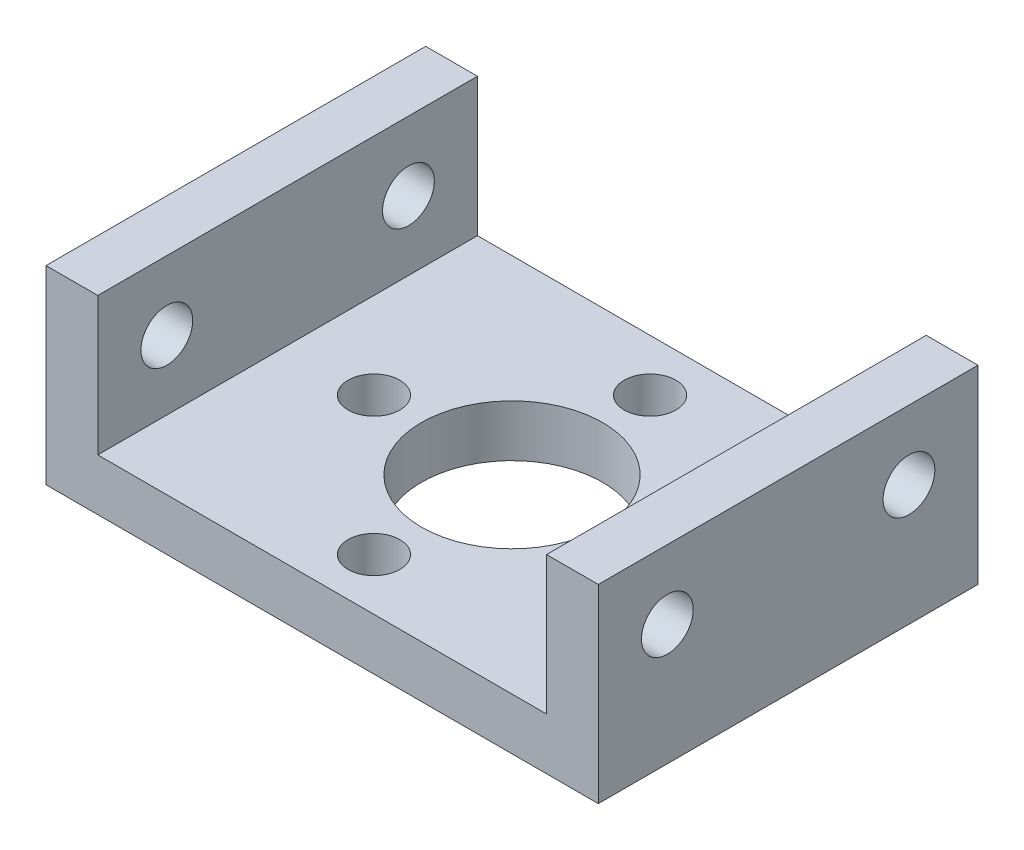
SolidWorks part; units mm, degrees
material "6061 合金"
ref_plane "前视基准面" through (0, 0, 0) normal (0, 0, 1) x (1, 0, 0)
ref_plane "上视基准面" through (0, 0, 0) normal (0, 1, 0) x (1, 0, 0)
ref_plane "右视基准面" through (0, 0, 0) normal (1, 0, 0) x (0, 0, -1)
sketch "草图1" plane through (0, 0, 0) normal (0, 1, 0) x (1, 0, 0)
  line L1 (-16, -11) -> (16, -11)
  line L2 (-16, -11) -> (-16, 11)
  line L3 (-16, 11) -> (16, 11)
  line L4 (16, -11) -> (16, 11)
  line L5 (-16, -11) -> (16, 11) construction
  line L6 (-16, 11) -> (16, -11) construction
  point P0 (0, 0)
  dimension "D1" = 32
  dimension "D2" = 22
extrude "凸台-拉伸1" add sketch "草图1" along normal blind 3
sketch "草图2" plane through (0, 3, 0) normal (0, 1, 0) x (1, 0, 0)
  line L0 (-16, -11) -> (16, -11) construction
  line L1 (-16, 11) -> (-13, 11)
  line L2 (-16, 11) -> (-16, -11)
  line L3 (-16, -11) -> (-13, -11)
  line L4 (-13, 11) -> (-13, -11)
  line L6 (16, 11) -> (13, 11)
  line L7 (16, 11) -> (16, -11)
  line L8 (16, -11) -> (13, -11)
  line L9 (13, 11) -> (13, -11)
  dimension "D1" = 3
  dimension "D2" = 3
extrude "凸台-拉伸2" add sketch "草图2" along normal blind 8
sketch "草图3" plane through (16, 0, 0) normal (1, 0, 0) x (0, 0, -1)
  line L0 (0, 11) -> (0, 7) construction
  line L1 (-11, 11) -> (11, 11) construction
  line L2 (-7, 7) -> (7, 7) construction
  circle A0 centre (-7, 7) radius 1.5
  circle A1 centre (7, 7) radius 1.5
  dimension "D3" = 3
  dimension "D4" = 3
  dimension "D1" = 14
  dimension "D2" = 4
extrude "切除-拉伸1" cut sketch "草图3" against normal through all
sketch "草图4" plane through (0, 3, 0) normal (0, 1, 0) x (1, 0, 0)
  circle A0 centre (0, 0) radius 5.25
  circle A1 centre (0, 0) radius 8 construction
  circle A2 centre (0, 8) radius 1.5
  circle A4 centre (8, 0) radius 1.5
  circle A5 centre (0, -8) radius 1.5
  circle A6 centre (-8, 0) radius 1.5
  point P15 (0, 0)
  dimension "D1" = 10.5
  dimension "D2" = 16
  dimension "D3" = 3
  dimension "D4" = 4
extrude "切除-拉伸2" cut sketch "草图4" against normal through all
